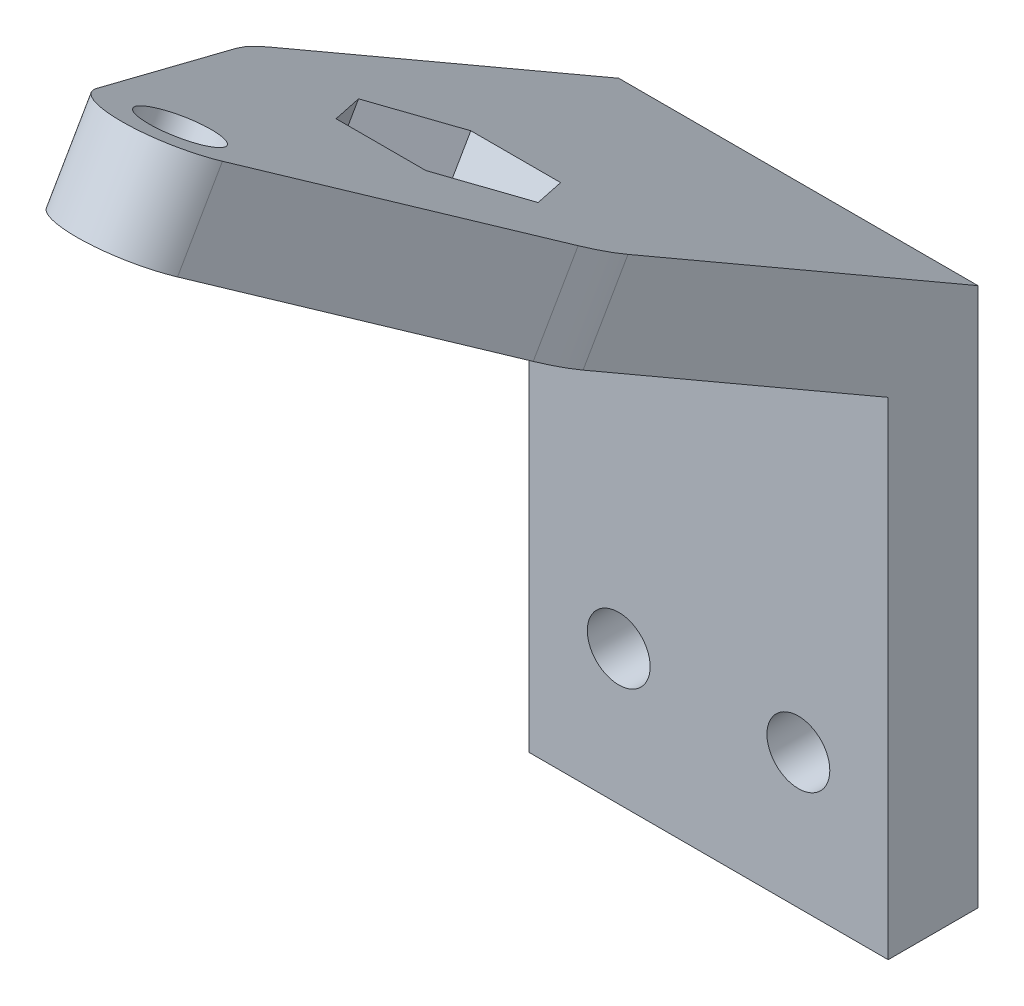
SolidWorks part; units mm, degrees
ref_plane "Front Plane" through (0, 0, 0) normal (0, 0, 1) x (1, 0, 0)
ref_plane "Top Plane" through (0, 0, 0) normal (0, 1, 0) x (1, 0, 0)
ref_plane "Right Plane" through (0, 0, 0) normal (1, 0, 0) x (0, 0, -1)
sketch "Sketch1" plane through (0, 0, 0) normal (1, 0, 0) x (0, 0, -1)
  line L0 (0, -60) -> (0, 0)
  line L1 (0, 0) -> (-75.3442, 43.5)
  dimension "D1" = 60
  dimension "D2" = 87
  dimension "D3" = 120
extrude "Extrude-Thin1" add sketch "Sketch1" along normal mid plane 40 thin thin type one direction reverse wall 10
sketch "Sketch2" plane through (0, 0, 0) normal (0, 0, -1) x (-1, 0, 0)
  line L0 (0, -60) -> (0, 0) construction
  line L1 (-20, -60) -> (20, -60) construction
  circle A0 centre (-10, -45) radius 3.5
  circle A1 centre (10, -45) radius 3.5
  dimension "D3" = 7
  dimension "D1" = 10
  dimension "D2" = 15
extrude "Cut-Extrude1" cut sketch "Sketch2" against normal up to next
sketch "Sketch3" plane through (0, 0, 0) normal (0, 0.866, -0.5) x (1, 0, 0)
  line L0 (0, 0) -> (0, -87) construction
  line L2 (20, 0) -> (-20, 0)
  line L3 (-20, 0) -> (-20, -45)
  line L4 (-20, 0) -> (-20, -87) construction
  line L5 (-19.0344, -50.2948) -> (-7.0172, -82.1474)
  line L6 (19.0344, -50.2948) -> (7.0172, -82.1474)
  line L7 (20, 0) -> (20, -45)
  line L10 (5, -36.3397) -> (-5, -36.3397)
  line L11 (-5, -36.3397) -> (-10, -45)
  line L12 (-10, -45) -> (-5, -53.6603)
  line L13 (-5, -53.6603) -> (5, -53.6603)
  line L14 (5, -53.6603) -> (10, -45)
  line L15 (10, -45) -> (5, -36.3397)
  line L16 (-20, -45) -> (-32.0344, -45)
  line L17 (-32.0344, -45) -> (-32.0344, -100.7818)
  line L18 (-32.0344, -100.7818) -> (29.7323, -100.7818)
  line L19 (29.7323, -100.7818) -> (29.7323, -45)
  line L20 (29.7323, -45) -> (20, -45)
  arc A0 (-20, -45) -> (-19.0344, -50.2948) centre (-5, -45) ccw
  arc A1 (-7.0172, -82.1474) -> (7.0172, -82.1474) centre (0, -79.5) ccw
  arc A2 (20, -45) -> (19.0344, -50.2948) centre (5, -45) cw
  circle A3 centre (0, -79.5) radius 4
  circle A4 centre (0, -45) radius 8.6603 construction
  line M6 (-20, 0) -> (-20, -87)
  line M7 (-20, -87) -> (20, -87)
  line M8 (20, -87) -> (20, 0)
  dimension "D2" = 15
  dimension "D3" = 7.5
  dimension "D5" = 8
  dimension "D1" = 20
  dimension "D4" = 0.9656
  dimension "D6" = 45
extrude "Cut-Extrude9" cut sketch "Sketch3" against normal blind 10 contours L19 L20 L16 L17 L18 M8 M7 M6 | A1 L5 A0 M6 M7 | A2 L6 A1 M8 M7
sketch "Sketch6" plane through (0, 0, 0) normal (0, 0.866, -0.5) x (1, 0, 0)
  line L0 (20, 0) -> (-20, 0) construction
  line L1 (10, -45) -> (5, -36.3397)
  line L2 (5, -36.3397) -> (-5, -36.3397)
  line L3 (-5, -36.3397) -> (-10, -45)
  line L4 (-10, -45) -> (-5, -53.6603)
  line L5 (-5, -53.6603) -> (5, -53.6603)
  line L6 (5, -53.6603) -> (10, -45)
  circle A0 centre (0, -79.5) radius 4
  arc A1 (-7.0172, -82.1474) -> (7.0172, -82.1474) centre (0, -79.5) ccw construction
  circle A2 centre (0, -45) radius 8.6603 construction
  point P16 (0, 0)
  dimension "D1" = 8
  dimension "D2" = 20
  dimension "D3" = 45
extrude "Cut-Extrude10" cut sketch "Sketch6" against normal blind 10
